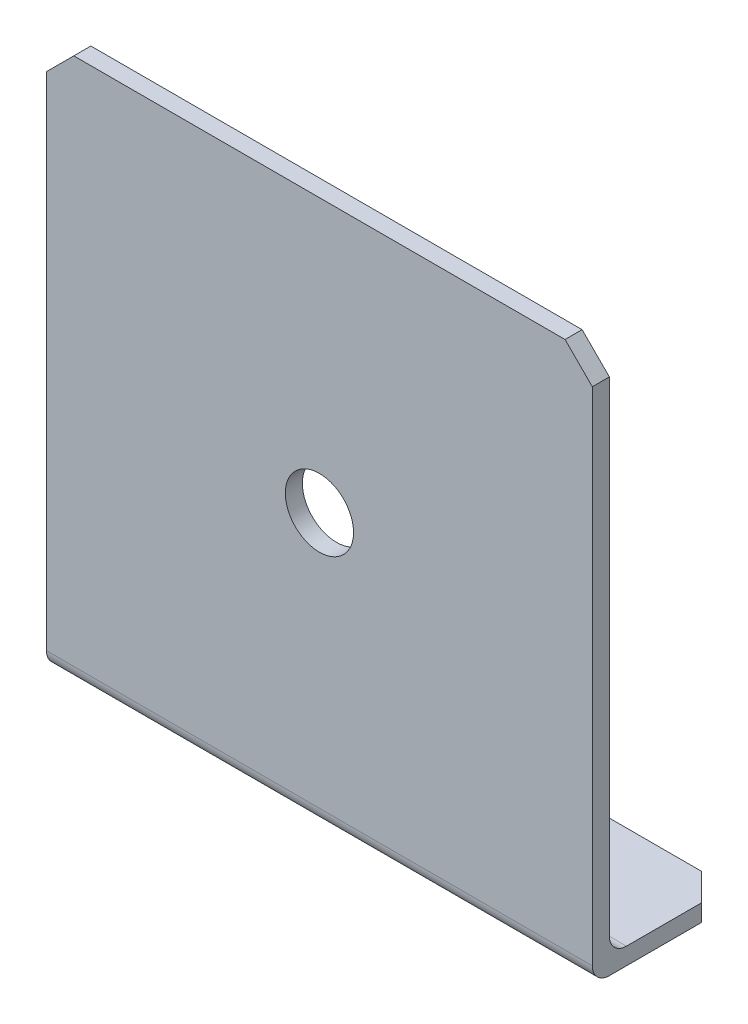
SolidWorks part; units mm, degrees
ref_plane "Front Plane" through (0, 0, 0) normal (0, 0, 1) x (1, 0, 0)
ref_plane "Top Plane" through (0, 0, 0) normal (0, 1, 0) x (1, 0, 0)
ref_plane "Right Plane" through (0, 0, 0) normal (1, 0, 0) x (0, 0, -1)
sketch "Sketch1" plane through (0, 0, 0) normal (1, 0, 0) x (0, 0, -1)
  line L0 (0, 1.5875) -> (0, 50.8)
  line L1 (0, 50.8) -> (1.5875, 50.8)
  line L2 (1.5875, 50.8) -> (1.5875, 3.175)
  line L3 (3.175, 1.5875) -> (12.7, 1.5875)
  line L4 (12.7, 1.5875) -> (12.7, 0)
  line L5 (12.7, 0) -> (1.5875, 0)
  arc A0 (3.175, 1.5875) -> (1.5875, 3.175) centre (3.175, 3.175) cw
  arc A1 (1.5875, 0) -> (0, 1.5875) centre (1.5875, 1.5875) cw
  point P11 (0, 0)
  dimension "D4" = 1.5875
  dimension "D5" = 1.5875
  dimension "D1" = 1.5875
  dimension "D2" = 50.8
  dimension "D3" = 12.7
extrude "Boss-Extrude1" add sketch "Sketch1" along normal blind 50.8
sketch "Sketch2" plane through (0, 0, 0) normal (0, -1, 0) x (1, 0, 0)
  line L0 (50.8, -1.5875) -> (50.8, -12.7) construction
  line L1 (50.8, 0) -> (0, 0) construction
  circle A0 centre (38.1, -6.35) radius 2.54
  circle A1 centre (12.7, -6.35) radius 2.54
  dimension "D4" = 5.08
  dimension "D1" = 25.4
  dimension "D2" = 12.7
  dimension "D3" = 6.35
extrude "Cut-Extrude1" cut sketch "Sketch2" against normal through all
sketch "Sketch3" plane through (0, 0, 0) normal (0, 0, 1) x (1, 0, 0)
  line L0 (25.4, 50.8) -> (25.4, 1.5875) construction
  line L1 (50.8, 50.8) -> (0, 50.8) construction
  line L2 (50.8, 1.5875) -> (0, 1.5875) construction
  line L3 (50.8, 0) -> (0, 0) construction
  circle A0 centre (25.4, 25.4) radius 3.175
  dimension "D1" = 6.35
  dimension "D2" = 25.4
extrude "Cut-Extrude2" cut sketch "Sketch3" against normal through all
chamfer "Chamfer1" distance 2.54 angle 45 4 edges at (0, 0.7937, -12.7) (0, 50.8, -0.7937) (50.8, 50.8, -0.7937) (50.8, 0.7937, -12.7)
